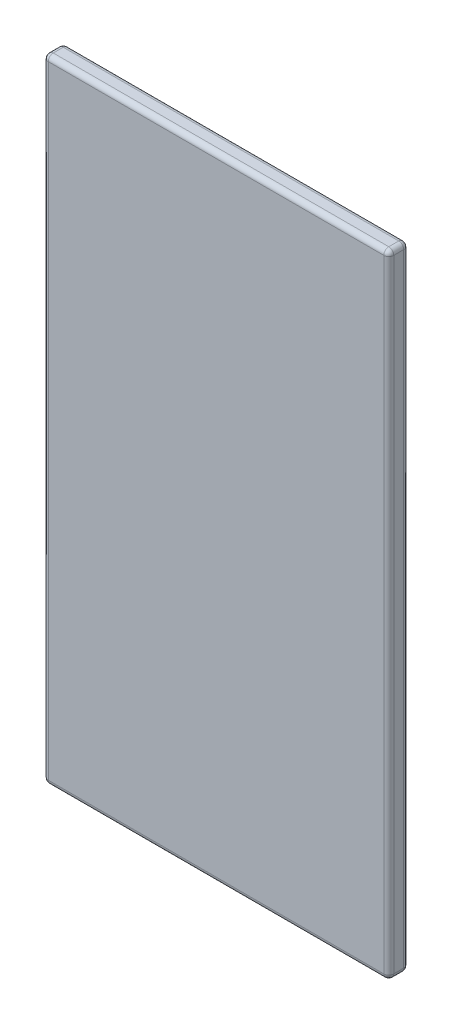
SolidWorks part; units mm, degrees
ref_plane "Front Plane" through (0, 0, 0) normal (0, 0, 1) x (1, 0, 0)
ref_plane "Top Plane" through (0, 0, 0) normal (0, 1, 0) x (1, 0, 0)
ref_plane "Right Plane" through (0, 0, 0) normal (1, 0, 0) x (0, 0, -1)
sketch "Sketch1" plane through (0, 0, 0) normal (0, 0, 1) x (1, 0, 0)
  line L1 (-17.35, -31.75) -> (17.35, -31.75)
  line L2 (-17.35, -31.75) -> (-17.35, 31.75)
  line L3 (-17.35, 31.75) -> (17.35, 31.75)
  line L4 (17.35, -31.75) -> (17.35, 31.75)
  line L5 (-17.35, -31.75) -> (17.35, 31.75) construction
  line L6 (-17.35, 31.75) -> (17.35, -31.75) construction
  point P0 (0, 0)
  dimension "D1" = 34.7
  dimension "D2" = 63.5
extrude "Boss-Extrude1" add sketch "Sketch1" along normal blind 2
fillet "Fillet1" radius 0.5 12 edges at (0, -31.75, 2) (0, -31.75, 0) (-17.35, 0, 2) (-17.35, -31.75, 1) (-17.35, 0, 0) (0, 31.75, 2) (-17.35, 31.75, 1) (0, 31.75, 0) (17.35, -31.75, 1) (17.35, 0, 2) (17.35, 31.75, 1) (17.35, 0, 0)
